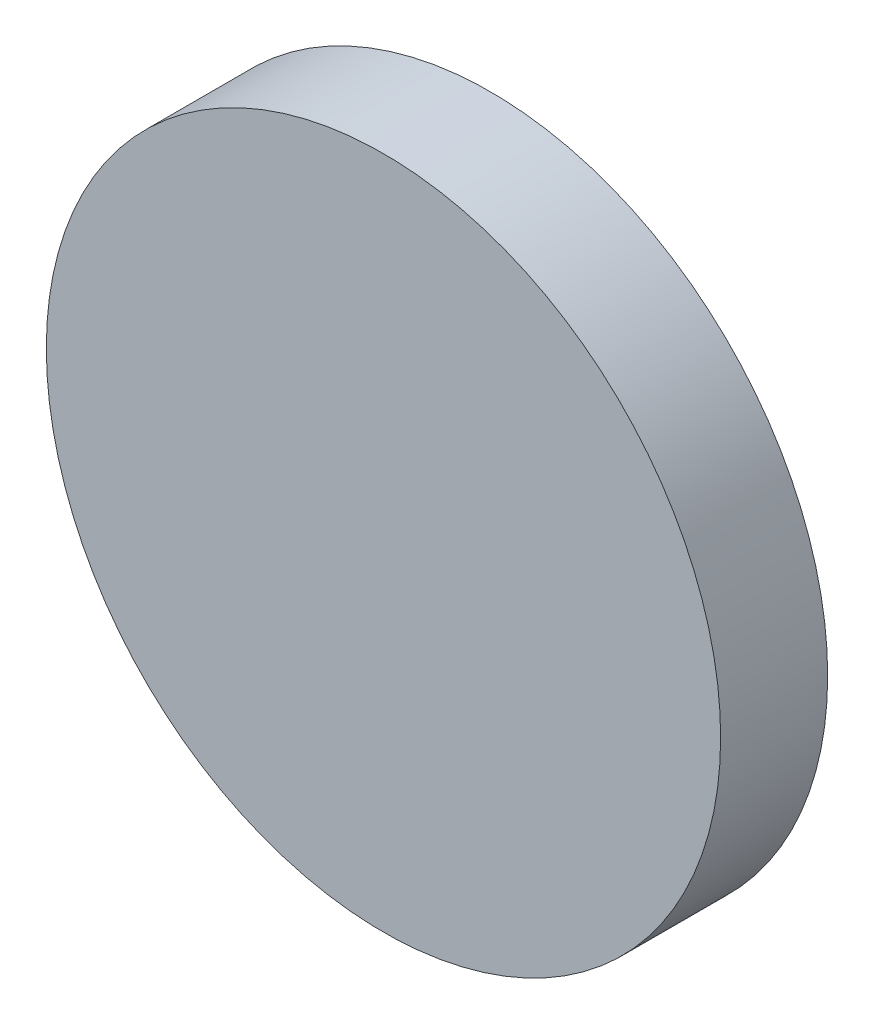
SolidWorks part; units mm, degrees
ref_plane "Front Plane" through (0, 0, 0) normal (0, 0, 1) x (1, 0, 0)
ref_plane "Top Plane" through (0, 0, 0) normal (0, 1, 0) x (1, 0, 0)
ref_plane "Right Plane" through (0, 0, 0) normal (1, 0, 0) x (0, 0, -1)
sketch "Sketch1" plane through (0, 0, 0) normal (0, 0, 1) x (1, 0, 0)
  circle A5 centre (93, -34.1) radius 6.3
extrude "Boss-Extrude1" add sketch "Sketch1" against normal blind 2
